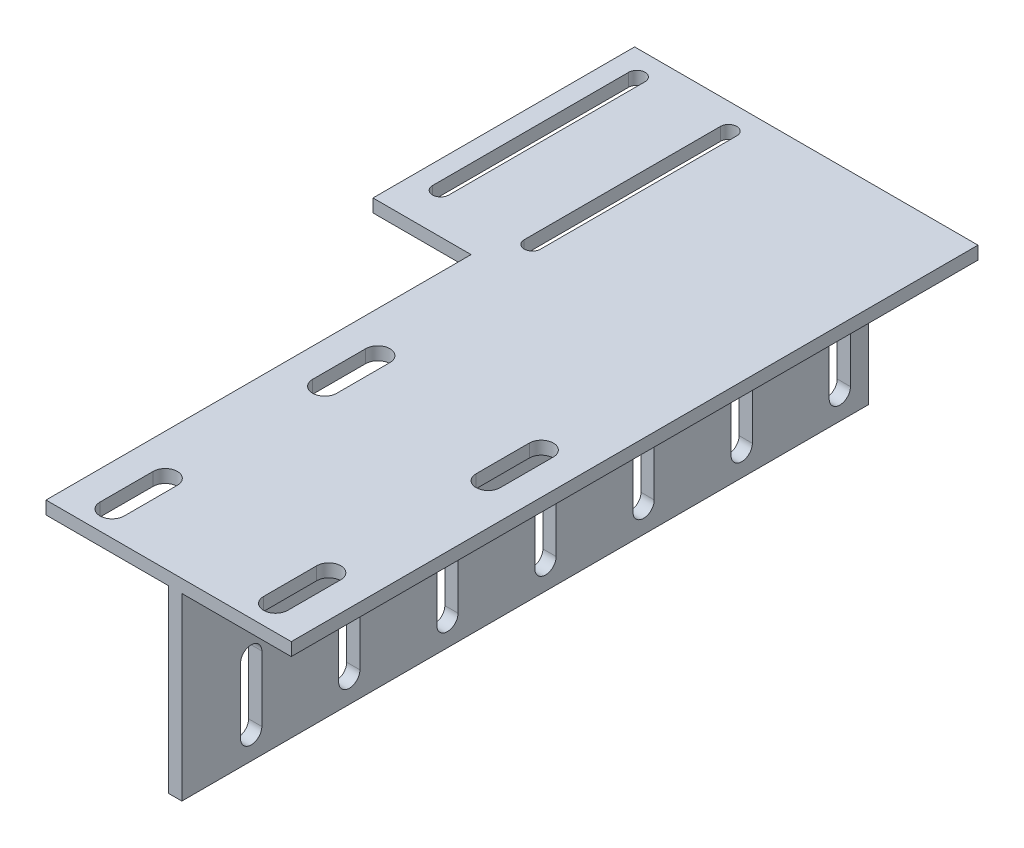
SolidWorks part; units mm, degrees
material "Fundición maleable"
ref_plane "Alzado" through (0, 0, 0) normal (0, 0, 1) x (1, 0, 0)
ref_plane "Planta" through (0, 0, 0) normal (0, 1, 0) x (1, 0, 0)
ref_plane "Vista lateral" through (0, 0, 0) normal (1, 0, 0) x (0, 0, -1)
sketch "Croquis1" plane through (0, 0, 0) normal (0, 1, 0) x (1, 0, 0)
  line L0 (-118.367, 194.7439) -> (-118.367, 74.7439) construction
  line L1 (-75, 210) -> (75, 210)
  line L2 (-75, 210) -> (-75, -210)
  line L3 (-75, -210) -> (75, -210)
  line L4 (75, 210) -> (75, -210)
  line L5 (-75, 210) -> (75, -210) construction
  line L6 (-75, -210) -> (75, 210) construction
  line L7 (-75, 210) -> (-135, 210)
  line L8 (-75, 210) -> (-75, 49.9767)
  line L9 (-75, 49.9767) -> (-135, 49.9767)
  line L10 (-135, 210) -> (-135, 49.9767)
  line L11 (-113.367, 194.7439) -> (-113.367, 74.7439)
  line L12 (-123.367, 194.7439) -> (-123.367, 74.7439)
  line L13 (-61.6427, 194.1336) -> (-61.6427, 74.1336) construction
  line L14 (-56.6427, 194.1336) -> (-56.6427, 74.1336)
  line L15 (-66.6427, 194.1336) -> (-66.6427, 74.1336)
  line L16 (-50.0129, -64.5448) -> (-50.0129, -32.05) construction
  line L17 (-57.3991, -64.5448) -> (-57.3991, -32.05)
  line L18 (-42.6268, -64.5448) -> (-42.6268, -32.05)
  line L19 (49.9871, -64.5448) -> (49.9871, -32.05) construction
  line L20 (42.6009, -64.5448) -> (42.6009, -32.05)
  line L21 (57.3732, -64.5448) -> (57.3732, -32.05)
  line L22 (49.9871, -194.5448) -> (49.9871, -162.05) construction
  line L23 (42.6009, -194.5448) -> (42.6009, -162.05)
  line L24 (57.3732, -194.5448) -> (57.3732, -162.05)
  line L25 (-50.0129, -194.5448) -> (-50.0129, -162.05) construction
  line L26 (-57.3991, -194.5448) -> (-57.3991, -162.05)
  line L27 (-42.6268, -194.5448) -> (-42.6268, -162.05)
  arc A0 (-113.367, 194.7439) -> (-123.367, 194.7439) centre (-118.367, 194.7439) ccw
  arc A1 (-123.367, 74.7439) -> (-113.367, 74.7439) centre (-118.367, 74.7439) ccw
  arc A2 (-56.6427, 194.1336) -> (-66.6427, 194.1336) centre (-61.6427, 194.1336) ccw
  arc A3 (-66.6427, 74.1336) -> (-56.6427, 74.1336) centre (-61.6427, 74.1336) ccw
  arc A4 (-57.3991, -64.5448) -> (-42.6268, -64.5448) centre (-50.0129, -64.5448) ccw
  arc A5 (-42.6268, -32.05) -> (-57.3991, -32.05) centre (-50.0129, -32.05) ccw
  arc A6 (42.6009, -64.5448) -> (57.3732, -64.5448) centre (49.9871, -64.5448) ccw
  arc A7 (57.3732, -32.05) -> (42.6009, -32.05) centre (49.9871, -32.05) ccw
  arc A8 (42.6009, -194.5448) -> (57.3732, -194.5448) centre (49.9871, -194.5448) ccw
  arc A9 (57.3732, -162.05) -> (42.6009, -162.05) centre (49.9871, -162.05) ccw
  arc A10 (-57.3991, -194.5448) -> (-42.6268, -194.5448) centre (-50.0129, -194.5448) ccw
  arc A11 (-42.6268, -162.05) -> (-57.3991, -162.05) centre (-50.0129, -162.05) ccw
  point P0 (0, 0)
  point P11 (-118.367, 134.7439)
  point P19 (-61.6427, 134.1336)
  point P25 (-50.0129, -48.2974)
  point P35 (49.9871, -48.2974)
  point P42 (49.9871, -178.2974)
  point P49 (-50.0129, -178.2974)
  dimension "D4" = 5
  dimension "D1" = 420
  dimension "D2" = 150
  dimension "D3" = 60
  dimension "D5" = 120
  dimension "D6" = 120
  dimension "D7" = 2
  dimension "D8" = 2
extrude "Saliente-Extruir1" add sketch "Croquis1" along normal blind 7.9375 contours L4 L1 L2 L3 | L7 L10 L9 L2
sketch "Croquis2" plane through (0, 0, 0) normal (0, -1, 0) x (1, 0, 0)
  line L0 (-75, 210) -> (75, 210) construction
  line L1 (8.0861, 210) -> (0, 210)
  line L2 (8.0861, 210) -> (8.0861, -210)
  line L3 (8.0861, -210) -> (0, -210)
  line L4 (0, 210) -> (0, -210)
  line L5 (8.0861, -620.3632) -> (8.0861, 279.6368) construction
  line L6 (-135, -210) -> (75, -210) construction
extrude "Saliente-Extruir2" add sketch "Croquis2" along normal blind 110
sketch "Croquis3" plane through (0, 0, 0) normal (-1, 0, 0) x (0, 0, 1)
  line L0 (-210, -74.9276) -> (210, -74.9276) construction
  line L1 (-210, -110) -> (-210, 0) construction
  line L2 (210, -110) -> (210, 0) construction
  line L3 (-192.4094, -54.9276) -> (-192.4094, -94.9276) construction
  line L4 (-185.9094, -54.9276) -> (-185.9094, -94.9276)
  line L5 (-198.9094, -54.9276) -> (-198.9094, -94.9276)
  line L6 (-132.4094, -54.9276) -> (-132.4094, -94.9276) construction
  line L7 (-125.9094, -54.9276) -> (-125.9094, -94.9276)
  line L8 (-138.9094, -54.9276) -> (-138.9094, -94.9276)
  line L9 (-72.4094, -54.9276) -> (-72.4094, -94.9276) construction
  line L10 (-65.9094, -54.9276) -> (-65.9094, -94.9276)
  line L11 (-78.9094, -54.9276) -> (-78.9094, -94.9276)
  line L12 (-12.4094, -54.9276) -> (-12.4094, -94.9276) construction
  line L13 (-5.9094, -54.9276) -> (-5.9094, -94.9276)
  line L14 (-18.9094, -54.9276) -> (-18.9094, -94.9276)
  line L15 (47.5906, -54.9276) -> (47.5906, -94.9276) construction
  line L16 (54.0906, -54.9276) -> (54.0906, -94.9276)
  line L17 (41.0906, -54.9276) -> (41.0906, -94.9276)
  line L18 (107.5906, -54.9276) -> (107.5906, -94.9276) construction
  line L19 (114.0906, -54.9276) -> (114.0906, -94.9276)
  line L20 (101.0906, -54.9276) -> (101.0906, -94.9276)
  line L21 (167.5906, -54.9276) -> (167.5906, -94.9276) construction
  line L22 (174.0906, -54.9276) -> (174.0906, -94.9276)
  line L23 (161.0906, -54.9276) -> (161.0906, -94.9276)
  arc A0 (-185.9094, -54.9276) -> (-198.9094, -54.9276) centre (-192.4094, -54.9276) ccw
  arc A1 (-198.9094, -94.9276) -> (-185.9094, -94.9276) centre (-192.4094, -94.9276) ccw
  arc A2 (-125.9094, -54.9276) -> (-138.9094, -54.9276) centre (-132.4094, -54.9276) ccw
  arc A3 (-138.9094, -94.9276) -> (-125.9094, -94.9276) centre (-132.4094, -94.9276) ccw
  arc A4 (-65.9094, -54.9276) -> (-78.9094, -54.9276) centre (-72.4094, -54.9276) ccw
  arc A5 (-78.9094, -94.9276) -> (-65.9094, -94.9276) centre (-72.4094, -94.9276) ccw
  arc A6 (-5.9094, -54.9276) -> (-18.9094, -54.9276) centre (-12.4094, -54.9276) ccw
  arc A7 (-18.9094, -94.9276) -> (-5.9094, -94.9276) centre (-12.4094, -94.9276) ccw
  arc A8 (54.0906, -54.9276) -> (41.0906, -54.9276) centre (47.5906, -54.9276) ccw
  arc A9 (41.0906, -94.9276) -> (54.0906, -94.9276) centre (47.5906, -94.9276) ccw
  arc A10 (114.0906, -54.9276) -> (101.0906, -54.9276) centre (107.5906, -54.9276) ccw
  arc A11 (101.0906, -94.9276) -> (114.0906, -94.9276) centre (107.5906, -94.9276) ccw
  arc A12 (174.0906, -54.9276) -> (161.0906, -54.9276) centre (167.5906, -54.9276) ccw
  arc A13 (161.0906, -94.9276) -> (174.0906, -94.9276) centre (167.5906, -94.9276) ccw
  point P8 (-192.4094, -74.9276)
  point P16 (-132.4094, -74.9276)
  point P23 (-72.4094, -74.9276)
  point P30 (-12.4094, -74.9276)
  point P37 (47.5906, -74.9276)
  point P44 (107.5906, -74.9276)
  point P51 (167.5906, -74.9276)
  dimension "D2" = 6.5
  dimension "D1" = 40
  dimension "D3" = 7
extrude "Cortar-Extruir1" cut sketch "Croquis3" against normal blind 10
